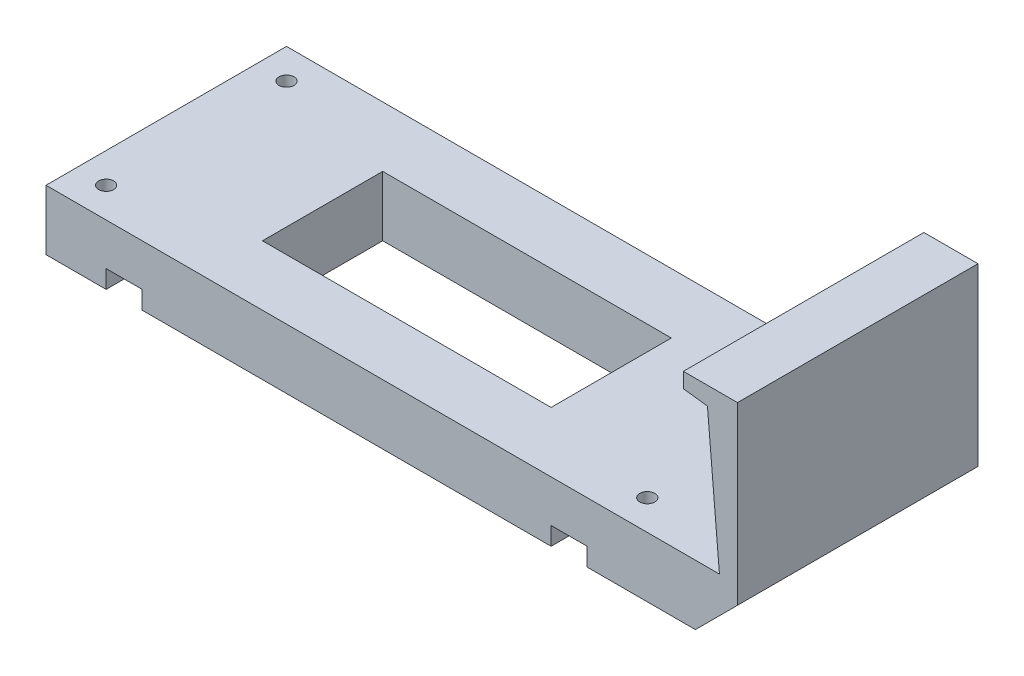
SolidWorks part; units mm, degrees
ref_plane "Plan de face" through (0, 0, 0) normal (0, 0, 1) x (1, 0, 0)
ref_plane "Plan de dessus" through (0, 0, 0) normal (0, 1, 0) x (1, 0, 0)
ref_plane "Plan de droite" through (0, 0, 0) normal (1, 0, 0) x (0, 0, -1)
sketch "Esquisse1" plane through (0, 0, 0) normal (0, 0, 1) x (1, 0, 0)
  line L0 (0, 0) -> (10, 0)
  line L1 (0, 10) -> (100, 10)
  line L2 (0, 10) -> (0, 0)
  line L3 (100, 10) -> (100, 0)
  line L4 (10, 0) -> (10, 3)
  line L5 (10, 3) -> (16, 3)
  line L6 (16, 3) -> (16, 0)
  line L7 (16, 0) -> (84, 0)
  line L8 (84, 0) -> (84, 3)
  line L9 (84, 3) -> (90, 3)
  line L10 (90, 3) -> (90, 0)
  line L11 (90, 0) -> (100, 0)
  dimension "D1" = 10
  dimension "D2" = 100
  dimension "D3" = 3
  dimension "D4" = 6
  dimension "D5" = 10
extrude "Boss.-Extru.1" add sketch "Esquisse1" along normal blind 40
sketch "Esquisse2" plane through (0, 10, 0) normal (0, 1, 0) x (1, 0, 0)
  line L1 (26, -10) -> (74, -10)
  line L2 (26, -10) -> (26, -30)
  line L3 (26, -30) -> (74, -30)
  line L4 (74, -10) -> (74, -30)
  line L5 (16, -40) -> (16, 0) construction
  line L6 (16, -40) -> (84, -40) construction
  line L7 (16, -40) -> (16, 0) construction
  line L8 (16, -40) -> (84, -40) construction
  point P8 (26, -20)
  point P9 (16, -20)
  point P10 (50, -40)
  point P11 (50, -30)
  dimension "D1" = 10
  dimension "D2" = 10
extrude "Enlèv. mat.-Extru.1" cut sketch "Esquisse2" against normal up to next
sketch "Esquisse3" plane through (0, 0, 0) normal (0, -1, 0) x (1, 0, 0)
  line L0 (0, 40) -> (10, 40) construction
  line L1 (90, 40) -> (100, 40) construction
  line L2 (5, 35) -> (5, 5) construction
  line L3 (0, 40) -> (0, 0) construction
  circle A0 centre (5, 35) radius 1.25
  circle A1 centre (5, 5) radius 1.25
  circle A2 centre (95, 35) radius 1.25
  circle A3 centre (95, 5) radius 1.25
  point P8 (5, 20)
  point P11 (5, 40)
  point P14 (0, 20)
  point P17 (95, 40)
  dimension "D2" = 2.5
  dimension "D1" = 30
extrude "Enlèv. mat.-Extru.2" cut sketch "Esquisse3" against normal up to next
sketch "Esquisse4" plane through (0, 0, 0) normal (0, 0, -1) x (-1, 0, 0)
  line L7 (-100, 10) -> (-112, 10)
  line L8 (-112, 10) -> (-110, 33.2)
  line L10 (-115, 36.2) -> (-115, 7)
  line L11 (-115, 7) -> (-108, 0)
  line L12 (-108, 0) -> (-100, 0)
  line L13 (-100, 0) -> (-100, 10)
  line L14 (-115, 36.2) -> (-106, 36.2)
  line L15 (-106, 36.2) -> (-106, 33.7)
  line L17 (-110, 33.2) -> (-106, 33.7)
  dimension "D1" = 10
  dimension "D2" = 12
  dimension "D3" = 3
  dimension "D4" = 3
  dimension "D5" = 135
  dimension "D6" = 23.2
  dimension "D7" = 4
  dimension "D8" = 0.5
extrude "Boss.-Extru.3" add sketch "Esquisse4" against normal up to vertex (40 mm away)
